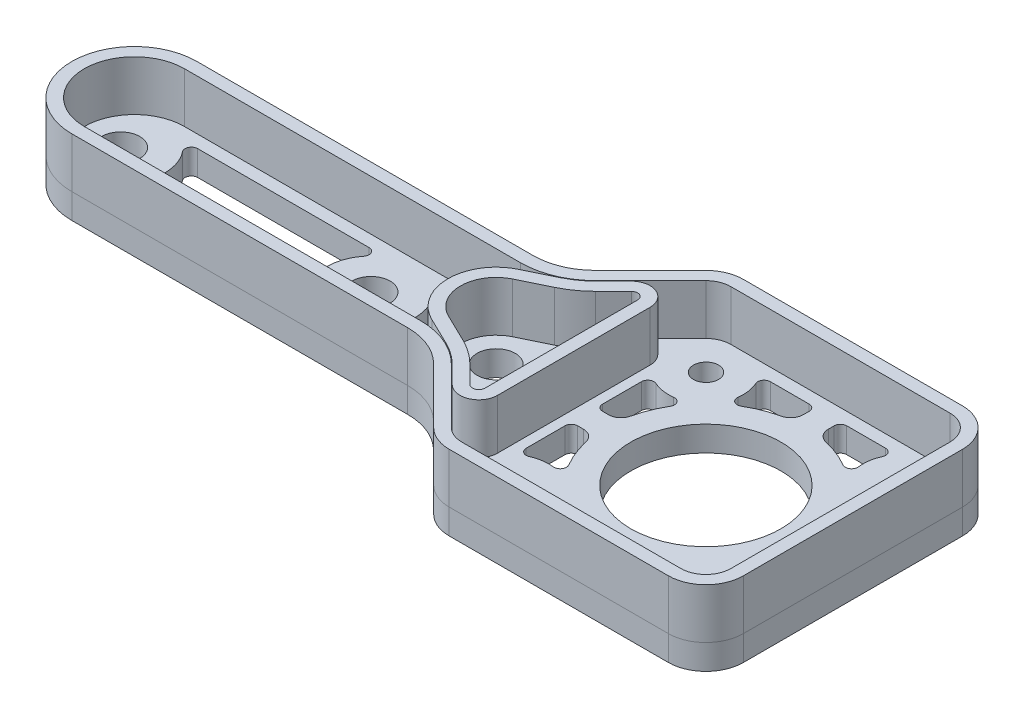
SolidWorks part; units mm, degrees
ref_plane "Front Plane" through (0, 0, 0) normal (0, 0, 1) x (1, 0, 0)
ref_plane "Top Plane" through (0, 0, 0) normal (0, 1, 0) x (1, 0, 0)
ref_plane "Right Plane" through (0, 0, 0) normal (1, 0, 0) x (0, 0, -1)
sketch "Sketch1" plane through (0, 0, 0) normal (0, 1, 0) x (1, 0, 0)
  line L1 (-21.5, 13.9196) -> (-21.5, 17.5) construction
  line L2 (-17.5, -21.5) -> (17.5, -21.5) construction
  line L3 (19.5, -3) -> (19.5, -9.2063)
  line L4 (19.5, 9.2063) -> (19.5, 3)
  line L5 (21.5, 21.5) -> (-21.5, -21.5) construction
  line L7 (-17.5, 21.5) -> (17.5, 21.5) construction
  line L8 (-11.4637, 10) -> (-11.4637, -10) construction
  line L9 (-11.4637, 10) -> (-11.4637, -10) construction
  line L10 (0, 0) -> (0, 15.6621) construction
  line L11 (0, 15.6621) -> (-15.6378, 15.6621) construction
  line L12 (-91.3, 10) -> (-37.6385, 10)
  line L13 (-91.3, -10) -> (-37.6385, -10)
  line L14 (-97.3, 0) -> (-101.3, 0) construction
  line L15 (-101.3, 0) -> (-91.3, 0) construction
  line L16 (-89.5, 10) -> (-37.6385, 10) construction
  line L17 (21.5, -17.5) -> (21.5, 17.5) construction
  line L18 (-59.8089, 6) -> (-87.1911, 6)
  line L19 (-47.1911, 6) -> (-39.8089, 6)
  line L20 (-47.1911, -6) -> (-39.8089, -6)
  line L21 (-21.5, -21.5) -> (21.5, 21.5) construction
  line L22 (18.5, 2) -> (17.5499, 2)
  line L23 (-87.1911, -6) -> (-59.8089, -6)
  line L24 (-17.5, 23.5) -> (17.5, 23.5)
  line L25 (23.5, -17.5) -> (23.5, 17.5)
  line L26 (-17.5, -23.5) -> (17.5, -23.5)
  line L27 (-89.5, -10) -> (-37.6385, -10) construction
  line L28 (-23.5, 10) -> (-23.5, 17.5) construction
  line L29 (-23.5, -17.5) -> (-23.5, -10) construction
  line L30 (18.5, -2) -> (17.5499, -2)
  line L31 (-3, -19.5) -> (-9.2063, -19.5)
  line L32 (9.2063, -19.5) -> (3, -19.5)
  line L33 (-23.4637, 0) -> (-16, 0) construction
  line L34 (2, -18.5) -> (2, -17.5499)
  line L35 (-2, -18.5) -> (-2, -17.5499)
  line L36 (-19.5, 3) -> (-19.5, 9.2063)
  line L37 (-19.5, -9.2063) -> (-19.5, -3)
  line L38 (-18.5, -2) -> (-17.5499, -2)
  line L39 (-9.2063, 19.5) -> (-3, 19.5)
  line L40 (-17.5, 19.5) -> (17.5, 19.5) construction
  line L41 (2, 18.5) -> (2, 17.5499)
  line L42 (-2, 18.5) -> (-2, 17.5499)
  line L43 (3, 19.5) -> (9.2063, 19.5)
  line L44 (0, 23.4637) -> (0, 16) construction
  line L45 (-18.5, 2) -> (-17.5499, 2)
  line L46 (-21.74, 21.7453) -> (-30.5718, 12.9245)
  line L47 (-21.74, -21.7453) -> (-30.5718, -12.9245)
  line L48 (-23.5, -3) -> (-23.5, -11.9221)
  line L49 (23.4637, 0) -> (16, 0) construction
  line L50 (-27.5, 0) -> (-21.5, 0) construction
  line L51 (-20.3267, -20.3302) -> (-29.1585, -11.5094) construction
  line L52 (-20.3267, -20.3302) -> (-20.3284, -20.3284)
  line L53 (-20.3267, 20.3302) -> (-29.1585, 11.5094) construction
  line L54 (0, -23.4637) -> (0, -16) construction
  line L55 (-26.0299, -2) -> (-24.5, -2)
  line L56 (-25.2067, -12.6296) -> (-30.1701, -7.6724)
  line L57 (-25.2067, 12.6296) -> (-30.1701, 7.6724)
  line L59 (-26.0299, 2) -> (-24.5, 2)
  line L61 (-18.9133, -18.9151) -> (-18.9142, -18.9142)
  line L62 (-18.9133, -18.9151) -> (-27.7452, -10.0943) construction
  line L64 (-23.5, 3) -> (-23.5, 11.9221)
  line L65 (-21.5, -17.5) -> (-21.5, -10) construction
  line L66 (-89.5, 8) -> (-37.6385, 8) construction
  line L67 (-89.5, -8) -> (-37.6385, -8) construction
  line L69 (-21.5, 10) -> (-21.5, 17.5) construction
  circle A0 centre (-93.5, 0) radius 2 construction
  arc A1 (-23.5, -17.5) -> (-17.5, -23.5) centre (-17.5, -17.5) ccw construction
  circle A2 centre (-33.5, 0) radius 2 construction
  arc A3 (-17.5, 21.5) -> (-21.5, 17.5) centre (-17.5, 17.5) ccw construction
  arc A4 (-21.5, -17.5) -> (-17.5, -21.5) centre (-17.5, -17.5) ccw construction
  arc A5 (-87.9748, -4.3789) -> (-87.9748, 4.3789) centre (-93.5, 0) ccw
  arc A6 (-47.9748, -4.3789) -> (-47.9748, 4.3789) centre (-53.5, 0) ccw
  circle A7 centre (-93.5, 0) radius 5.8 construction
  arc A8 (-39.0252, 4.3789) -> (-39.0252, -4.3789) centre (-33.5, 0) ccw
  arc A9 (-17.5, 23.5) -> (-23.5, 17.5) centre (-17.5, 17.5) ccw construction
  circle A10 centre (0, 0) radius 12
  circle A11 centre (-15.6378, 15.6621) radius 2
  circle A12 centre (15.6621, 15.6378) radius 2
  circle A13 centre (-93.5, 0) radius 7.05 construction
  arc A14 (21.5, -17.5) -> (17.5, -21.5) centre (17.5, -17.5) cw construction
  arc A15 (17.5, 21.5) -> (21.5, 17.5) centre (17.5, 17.5) cw construction
  arc A17 (17.5, 23.5) -> (23.5, 17.5) centre (17.5, 17.5) cw
  arc A18 (23.5, -17.5) -> (17.5, -23.5) centre (17.5, -17.5) cw
  circle A20 centre (15.6378, -15.6621) radius 2
  circle A21 centre (-15.6621, -15.6378) radius 2
  circle A22 centre (-53.5, 0) radius 2 construction
  circle A23 centre (-53.5, 0) radius 7.05 construction
  arc A24 (-59.0252, 4.3789) -> (-59.0252, -4.3789) centre (-53.5, 0) ccw
  circle A25 centre (-33.5, 0) radius 7.05 construction
  arc A26 (-26.9579, 2.6273) -> (-29.9649, 6.0996) centre (-33.5, 0) ccw
  arc A27 (-17.5, 23.5) -> (-21.74, 21.7453) centre (-17.5, 17.5) ccw
  arc A28 (-30.1701, 7.6724) -> (-29.9649, 6.0996) centre (-29.4635, 6.9648) ccw
  arc A29 (-26.0299, 2) -> (-26.9579, 2.6273) centre (-26.0299, 3) cw
  arc A30 (-87.9748, 4.3789) -> (-87.1911, 6) centre (-87.1911, 5) cw
  arc A31 (-91.3, 10) -> (-91.3, -10) centre (-91.3, 0) ccw
  arc A32 (13.7831, -8.1256) -> (15.5999, -3.5556) centre (0, 0) ccw
  arc A33 (13.7831, -8.1256) -> (14.7756, -9.6248) centre (14.6446, -8.6335) ccw
  arc A34 (18.0864, -10.1167) -> (14.7756, -9.6248) centre (15.5724, -15.6501) ccw
  arc A35 (17.5499, -2) -> (15.5999, -3.5556) centre (17.5499, -4) ccw
  arc A36 (18.0864, -10.1167) -> (19.5, -9.2063) centre (18.5, -9.2063) ccw
  arc A37 (19.5, -3) -> (18.5, -2) centre (18.5, -3) ccw
  arc A38 (18.0864, 10.1167) -> (14.7756, 9.6248) centre (15.5724, 15.6501) cw
  arc A39 (17.5499, 2) -> (15.5999, 3.5556) centre (17.5499, 4) cw
  arc A40 (13.7831, 8.1256) -> (14.7756, 9.6248) centre (14.6446, 8.6335) cw
  arc A41 (13.7831, 8.1256) -> (15.5999, 3.5556) centre (0, 0) cw
  arc A42 (18.5, 2) -> (19.5, 3) centre (18.5, 3) ccw
  arc A43 (18.0864, 10.1167) -> (19.5, 9.2063) centre (18.5, 9.2063) cw
  arc A44 (-8.1256, -13.7831) -> (-3.5556, -15.5999) centre (0, 0) ccw
  arc A45 (-10.1167, 18.0864) -> (-9.6248, 14.7756) centre (-15.6501, 15.5724) cw
  arc A46 (8.1256, 13.7831) -> (3.5556, 15.5999) centre (0, 0) ccw
  arc A47 (-8.1256, -13.7831) -> (-9.6248, -14.7756) centre (-8.6335, -14.6446) ccw
  arc A48 (8.1256, 13.7831) -> (9.6248, 14.7756) centre (8.6335, 14.6446) ccw
  arc A49 (10.1167, 18.0864) -> (9.6248, 14.7756) centre (15.6501, 15.5724) ccw
  arc A50 (2, 17.5499) -> (3.5556, 15.5999) centre (4, 17.5499) ccw
  arc A51 (-2, 17.5499) -> (-3.5556, 15.5999) centre (-4, 17.5499) cw
  arc A52 (-10.1167, -18.0864) -> (-9.6248, -14.7756) centre (-15.6501, -15.5724) ccw
  arc A53 (-8.1256, 13.7831) -> (-9.6248, 14.7756) centre (-8.6335, 14.6446) cw
  arc A54 (-2, -17.5499) -> (-3.5556, -15.5999) centre (-4, -17.5499) ccw
  arc A55 (-8.1256, 13.7831) -> (-3.5556, 15.5999) centre (0, 0) cw
  arc A56 (-10.1167, -18.0864) -> (-9.2063, -19.5) centre (-9.2063, -18.5) ccw
  arc A57 (-3, -19.5) -> (-2, -18.5) centre (-3, -18.5) ccw
  arc A58 (10.1167, -18.0864) -> (9.6248, -14.7756) centre (15.6501, -15.5724) cw
  arc A59 (2, -17.5499) -> (3.5556, -15.5999) centre (4, -17.5499) cw
  arc A60 (8.1256, -13.7831) -> (9.6248, -14.7756) centre (8.6335, -14.6446) cw
  arc A61 (8.1256, -13.7831) -> (3.5556, -15.5999) centre (0, 0) cw
  arc A62 (2, -18.5) -> (3, -19.5) centre (3, -18.5) ccw
  arc A63 (10.1167, -18.0864) -> (9.2063, -19.5) centre (9.2063, -18.5) cw
  arc A64 (-13.7831, 8.1256) -> (-15.5999, 3.5556) centre (0, 0) ccw
  arc A65 (-13.7831, 8.1256) -> (-14.7756, 9.6248) centre (-14.6446, 8.6335) ccw
  arc A66 (-18.0864, 10.1167) -> (-14.7756, 9.6248) centre (-15.5724, 15.6501) ccw
  arc A67 (-17.5499, 2) -> (-15.5999, 3.5556) centre (-17.5499, 4) ccw
  arc A68 (-18.0864, 10.1167) -> (-19.5, 9.2063) centre (-18.5, 9.2063) ccw
  arc A69 (-19.5, 3) -> (-18.5, 2) centre (-18.5, 3) ccw
  arc A70 (-18.0864, -10.1167) -> (-14.7756, -9.6248) centre (-15.5724, -15.6501) cw
  arc A71 (-17.5499, -2) -> (-15.5999, -3.5556) centre (-17.5499, -4) cw
  arc A72 (-13.7831, -8.1256) -> (-14.7756, -9.6248) centre (-14.6446, -8.6335) cw
  arc A73 (10.1167, 18.0864) -> (9.2063, 19.5) centre (9.2063, 18.5) ccw
  arc A74 (-13.7831, -8.1256) -> (-15.5999, -3.5556) centre (0, 0) cw
  arc A75 (-18.5, -2) -> (-19.5, -3) centre (-18.5, -3) ccw
  arc A76 (3, 19.5) -> (2, 18.5) centre (3, 18.5) ccw
  arc A77 (-18.0864, -10.1167) -> (-19.5, -9.2063) centre (-18.5, -9.2063) cw
  arc A78 (-2, 18.5) -> (-3, 19.5) centre (-3, 18.5) ccw
  arc A79 (-21.74, -21.7453) -> (-17.5, -23.5) centre (-17.5, -17.5) ccw
  arc A80 (-10.1167, 18.0864) -> (-9.2063, 19.5) centre (-9.2063, 18.5) cw
  arc A81 (-17.5, 23.5) -> (-23.5, 17.5) centre (-17.5, 17.5) ccw construction
  arc A82 (-23.5, -17.5) -> (-17.5, -23.5) centre (-17.5, -17.5) ccw construction
  arc A83 (-37.6385, -10) -> (-30.5718, -12.9245) centre (-37.6385, -20) cw
  arc A84 (-37.6385, 10) -> (-30.5718, 12.9245) centre (-37.6385, 20) ccw
  arc A85 (-87.1911, -6) -> (-87.9748, -4.3789) centre (-87.1911, -5) cw
  arc A86 (-59.8089, -6) -> (-59.0252, -4.3789) centre (-59.8089, -5) ccw
  arc A87 (-59.8089, 6) -> (-59.0252, 4.3789) centre (-59.8089, 5) cw
  arc A88 (-47.1911, 6) -> (-47.9748, 4.3789) centre (-47.1911, 5) ccw
  arc A89 (-47.1911, -6) -> (-47.9748, -4.3789) centre (-47.1911, -5) cw
  arc A90 (-89.5, 8) -> (-89.5, -8) centre (-89.5, 0) ccw construction
  arc A91 (-37.6385, 8) -> (-29.1585, 11.5094) centre (-37.6385, 20) ccw construction
  arc A92 (-37.6385, -8) -> (-29.1585, -11.5094) centre (-37.6385, -20) cw construction
  arc A93 (-17.5, 21.5) -> (-20.3267, 20.3302) centre (-17.5, 17.5) ccw construction
  arc A94 (-20.3267, -20.3302) -> (-17.5, -21.5) centre (-17.5, -17.5) ccw construction
  arc A95 (-24.5, 2) -> (-23.5, 3) centre (-24.5, 3) ccw
  arc A96 (-23.5, 11.9221) -> (-25.2067, 12.6296) centre (-24.5, 11.9221) ccw
  arc A97 (-39.8089, -6) -> (-39.0252, -4.3789) centre (-39.8089, -5) ccw
  arc A98 (-39.8089, 6) -> (-39.0252, 4.3789) centre (-39.8089, 5) cw
  arc A99 (-23.5, -11.9221) -> (-25.2067, -12.6296) centre (-24.5, -11.9221) cw
  circle A100 centre (-53.5, 0) radius 3.05
  arc A101 (-24.5, -2) -> (-23.5, -3) centre (-24.5, -3) cw
  arc A102 (-26.0299, -2) -> (-26.9579, -2.6273) centre (-26.0299, -3) ccw
  arc A103 (-89.5, 10) -> (-89.5, -10) centre (-89.5, 0) ccw construction
  arc A104 (-30.1701, -7.6724) -> (-29.9649, -6.0996) centre (-29.4635, -6.9648) cw
  arc A105 (-26.9579, -2.6273) -> (-29.9649, -6.0996) centre (-33.5, 0) cw
  circle A110 centre (-33.5, 0) radius 3.05
  circle A111 centre (-93.5, 0) radius 3.05
  point P0 (0.0699, 0.0699)
  point P5 (0, 0)
  point P33 (-53.5, 6)
  point P43 (-53.5, -6)
  point P51 (0, 0)
  point P77 (-93.5, -6)
  point P80 (-93.5, 6)
  point P119 (-11.2855, 11.3418)
  point P207 (0, 0)
  point P227 (0, 0)
  point P238 (-26.7396, 2)
  point P244 (-21.5, -16.3317)
  point P251 (-57.2017, 6)
  point P264 (-34.8226, -5.8524)
  point P265 (-48.516, -6)
  point P283 (-26.7396, -2)
  point P289 (-25.9608, -2)
  dimension "D3" = 4
  dimension "D4" = 4
  dimension "D5" = 2
  dimension "D9" = 1
  dimension "D14" = 4
  dimension "D7" = 10
  dimension "D2" = 2
  dimension "D6" = 2
  dimension "D8" = 2
  dimension "D10" = 4
  dimension "D16" = 4
  dimension "D17" = 4
extrude "Boss-Extrude1" add sketch "Sketch1" along normal blind 4
sketch "Sketch4" plane through (0, 4, 0) normal (0, 1, 0) x (1, 0, 0)
  line L14 (-37.6385, 10) -> (-91.3, 10)
  line L15 (-91.3, -10) -> (-37.6385, -10)
  line L16 (-30.5718, -12.9245) -> (-21.74, -21.7453)
  line L17 (-17.5, -23.5) -> (17.5, -23.5)
  line L18 (23.5, -17.5) -> (23.5, 17.5)
  line L19 (17.5, 23.5) -> (-17.5, 23.5)
  line L20 (-21.74, 21.7453) -> (-30.5718, 12.9245)
  line L21 (-37.6385, 10) -> (-91.3, 10)
  line L22 (-91.3, -10) -> (-37.6385, -10)
  line L23 (-30.5718, -12.9245) -> (-21.74, -21.7453)
  line L25 (-17.5, -23.5) -> (17.5, -23.5)
  line L26 (23.5, -17.5) -> (23.5, 17.5)
  line L27 (17.5, 23.5) -> (-17.5, 23.5)
  line L28 (-21.74, 21.7453) -> (-30.5718, 12.9245)
  arc A14 (-37.6385, 10) -> (-30.5718, 12.9245) centre (-37.6385, 20) ccw
  arc A15 (-91.3, 10) -> (-91.3, -10) centre (-91.3, 0) ccw
  arc A16 (-30.5718, -12.9245) -> (-37.6385, -10) centre (-37.6385, -20) ccw
  arc A17 (-21.74, -21.7453) -> (-17.5, -23.5) centre (-17.5, -17.5) ccw
  arc A18 (17.5, -23.5) -> (23.5, -17.5) centre (17.5, -17.5) ccw
  arc A19 (23.5, 17.5) -> (17.5, 23.5) centre (17.5, 17.5) ccw
  arc A20 (-17.5, 23.5) -> (-21.74, 21.7453) centre (-17.5, 17.5) ccw
  arc A21 (-37.6385, 10) -> (-30.5718, 12.9245) centre (-37.6385, 20) ccw
  arc A22 (-91.3, 10) -> (-91.3, -10) centre (-91.3, 0) ccw
  arc A23 (-30.5718, -12.9245) -> (-37.6385, -10) centre (-37.6385, -20) ccw
  arc A24 (-21.74, -21.7453) -> (-17.5, -23.5) centre (-17.5, -17.5) ccw
  arc A25 (17.5, -23.5) -> (23.5, -17.5) centre (17.5, -17.5) ccw
  arc A26 (23.5, 17.5) -> (17.5, 23.5) centre (17.5, 17.5) ccw
  arc A27 (-17.5, 23.5) -> (-21.74, 21.7453) centre (-17.5, 17.5) ccw
  dimension "D1" = 0
extrude "Extrude-Thin1" add sketch "Sketch4" along normal blind 8 separate body thin thin type one direction reverse wall 2
sketch "Sketch5" plane through (0, 4, 0) normal (0, 1, 0) x (1, 0, 0)
  line L0 (-20.3267, 20.3302) -> (-29.1585, 11.5094) construction
  line L1 (-26.22, 14.4442) -> (-29.1585, 11.5094) construction
  line L2 (-26.22, 14.3029) -> (-29.0878, 11.4387)
  line L3 (-21.1, -12.1803) -> (-21.1, 12.1803)
  line L4 (-21.5, 13.9196) -> (-21.5, 17.5) construction
  line L5 (-21.5, -14.3342) -> (-21.5, 14.3342) construction
  line L6 (-32.3993, 9.2041) -> (-36.9054, 7.0173) construction
  line L7 (-32.3993, -9.2041) -> (-36.9054, -7.0173) construction
  line L8 (-29.1585, -11.5094) -> (-26.22, -14.4442) construction
  line L9 (-21.1, -14.3342) -> (-21.1, 14.3342) construction
  line L10 (-32.3557, 9.1141) -> (-36.8618, 6.9274)
  line L11 (-32.3557, -9.1141) -> (-36.8618, -6.9274)
  line L12 (-29.0878, -11.4387) -> (-26.22, -14.3029)
  line L13 (-29.0878, -11.4387) -> (-26.1493, -14.3735) construction
  line L14 (-26.1493, 14.3735) -> (-29.0878, 11.4387) construction
  arc A0 (-32.3557, 9.1141) -> (-29.0878, 11.4387) centre (-37.6385, 20) ccw
  arc A1 (-36.9054, 7.0173) -> (-36.9054, -7.0173) centre (-33.5, 0) ccw construction
  arc A2 (-36.8618, 6.9274) -> (-36.8618, -6.9274) centre (-33.5, 0) ccw
  arc A3 (-29.0878, -11.4387) -> (-32.3557, -9.1141) centre (-37.6385, -20) ccw
  arc A4 (-26.22, -14.3029) -> (-21.1, -12.1803) centre (-24.1, -12.1803) ccw
  arc A5 (-26.22, 14.3029) -> (-21.1, 12.1803) centre (-24.1, 12.1803) cw
  arc A6 (-29.1585, -11.5094) -> (-37.6385, -8) centre (-37.6385, -20) ccw construction
  arc A7 (-37.6385, 8) -> (-29.1585, 11.5094) centre (-37.6385, 20) ccw construction
  arc A8 (-29.1585, -11.5094) -> (-32.3993, -9.2041) centre (-37.6385, -20) ccw construction
  arc A9 (-32.3993, 9.2041) -> (-29.1585, 11.5094) centre (-37.6385, 20) ccw construction
  dimension "D1" = 0.4
  dimension "D2" = 0.1
  dimension "D3" = 3
extrude "Extrude-Thin2" add sketch "Sketch5" along normal blind 8 separate body thin thin type one direction reverse wall 2
sketch "Sketch6" plane through (0, 0, 0) normal (0, 1, 0) x (1, 0, 0)
  line L0 (-33.5, 0) -> (-23.5, 0) construction
  line L1 (-91.3, 10) -> (-37.6385, 10) construction
  line L2 (-23.5, -30) -> (-63.5, -30)
  line L3 (-23.5, -30) -> (-23.5, 10)
  line L4 (-23.5, 10) -> (-63.5, 10)
  line L7 (-63.5, 10) -> (-103.5, 10)
  line L9 (-63.5, -30) -> (-103.5, -30)
  line L10 (-103.5, 10) -> (-103.5, -30)
